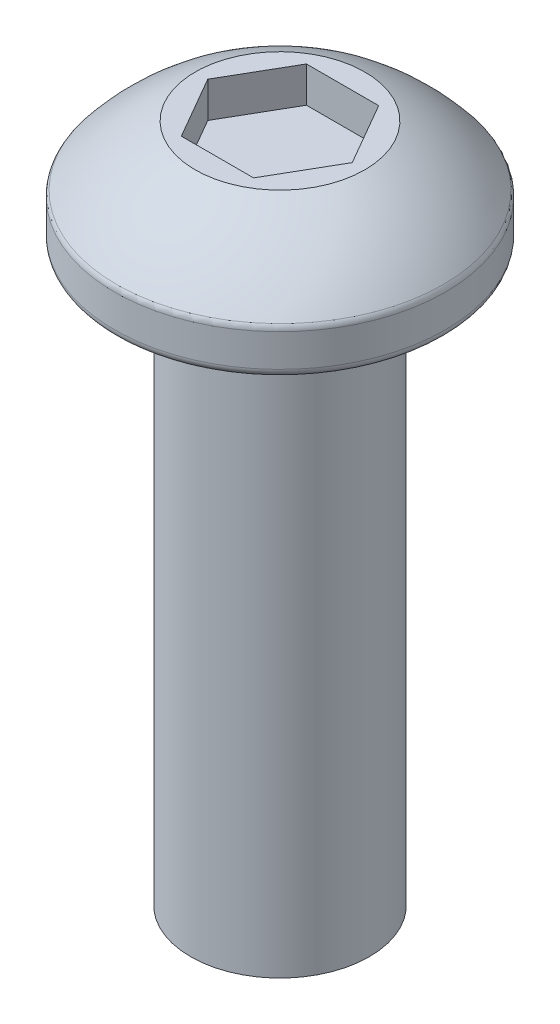
SolidWorks part; units mm, degrees
ref_plane "Front Plane" through (0, 0, 0) normal (0, 0, 1) x (1, 0, 0)
ref_plane "Top Plane" through (0, 0, 0) normal (0, 1, 0) x (1, 0, 0)
ref_plane "Right Plane" through (0, 0, 0) normal (1, 0, 0) x (0, 0, -1)
sketch "Sketch1" plane through (0, 0, 0) normal (0, 0, 1) x (1, 0, 0)
  line L0 (0, 21.3223) -> (0, -43.638) construction
sketch "Sketch2" plane through (0, 0, 0) normal (0, 0, 1) x (1, 0, 0)
  line L1 (0, 200021.3223) -> (0, -200043.638) construction
  line L3 (4.625, 0) -> (2.5, 0)
  line L4 (2.5, 0) -> (2.5, -16)
  line L5 (2.5, -16) -> (0, -16)
  line L6 (0, -16) -> (0, 3.5)
  line L7 (4.625, 0) -> (4.625, 1.25)
  circle A0 centre (0, -2.3785) radius 5.8785
  point P1 (0, 2.2151)
  dimension "D1" = 2.5
  dimension "D2" = 1.25
  dimension "D3" = 3.5
  dimension "D4" = 16
  dimension "D5" = 4.625
revolve "Revolve1" add sketch "Sketch2" angle 360 about L0
sketch "Sketch3" plane through (0, 0, 0) normal (0, 1, 0) x (1, 0, 0)
  line L0 (0, 0) -> (2.0207, 0) construction
  line L1 (2.0207, 0) -> (1.0104, 1.75)
  line L2 (1.0104, 1.75) -> (-1.0104, 1.75)
  line L3 (-1.0104, 1.75) -> (-2.0207, 0)
  line L4 (-2.0207, 0) -> (-1.0104, -1.75)
  line L5 (-1.0104, -1.75) -> (1.0104, -1.75)
  line L6 (1.0104, -1.75) -> (2.0207, 0)
  circle A0 centre (0, 0) radius 1.75 construction
  dimension "D1" = 3.5
extrude "Cut-Extrude1" cut sketch "Sketch3" along normal blind 3 from offset 2
fillet "Fillet1" radius 0.25 3 edges at (-2.5, 0, 0) (-4.625, 0, 0) (-4.625, 1.25, 0)
sketch "Sketch4" plane through (0, 0, 0) normal (0, 0, 1) x (1, 0, 0)
  line L0 (0, 0) -> (0, 3) construction
  line L1 (-4.625, 5) -> (4.625, 5)
  line L2 (-4.625, 5) -> (-4.625, 3)
  line L3 (-4.625, 3) -> (4.625, 3)
  line L4 (4.625, 5) -> (4.625, 3)
  line L5 (-4.625, 1.1626) -> (-4.625, 3) construction
  line L6 (4.625, 1.1626) -> (4.625, 3) construction
  dimension "D1" = 3
  dimension "D2" = 2
extrude "Cut-Extrude2" cut sketch "Sketch4" against normal through all both and the other way through all
